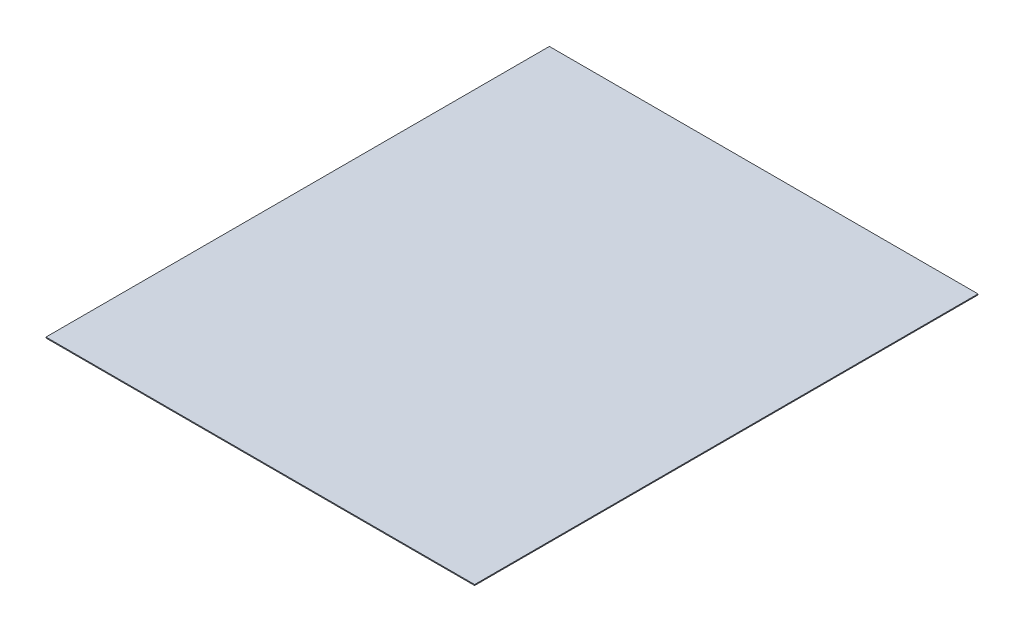
SolidWorks part; units mm, degrees
ref_plane "Front Plane" through (0, 0, 0) normal (0, 0, 1) x (1, 0, 0)
ref_plane "Top Plane" through (0, 0, 0) normal (0, 1, 0) x (1, 0, 0)
ref_plane "Right Plane" through (0, 0, 0) normal (1, 0, 0) x (0, 0, -1)
other "Configuration Table"
sketch "Sketch1" plane through (0, 0, 0) normal (0, 0, 1) x (1, 0, 0)
  line L1 (1.5, 120) -> (698.5, 120)
  line L2 (1.5, 120) -> (1.5, 121.5)
  line L3 (1.5, 121.5) -> (698.5, 121.5)
  line L4 (698.5, 120) -> (698.5, 121.5)
extrude "PRESS_dis_alt_1" add sketch "Sketch1" against normal blind 818.5 separate body
